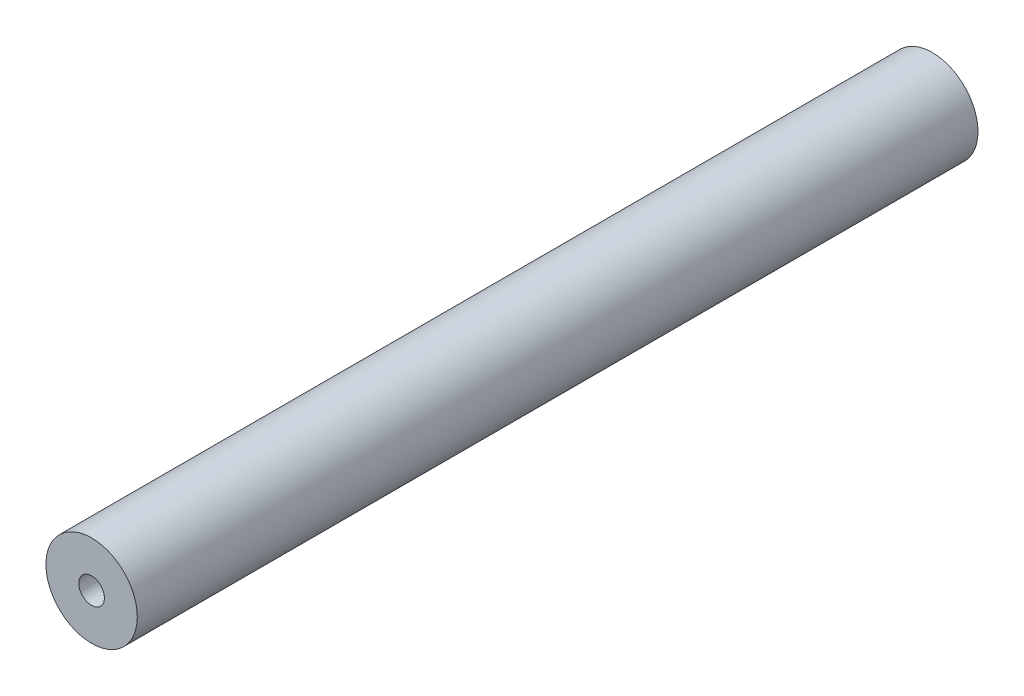
SolidWorks part; units mm, degrees
ref_plane "Front Plane" through (0, 0, 0) normal (0, 0, 1) x (1, 0, 0)
ref_plane "Top Plane" through (0, 0, 0) normal (0, 1, 0) x (1, 0, 0)
ref_plane "Right Plane" through (0, 0, 0) normal (1, 0, 0) x (0, 0, -1)
sketch "Sketch1" plane through (0, 0, 0) normal (0, 0, 1) x (1, 0, 0)
  circle A0 centre (0, 0) radius 31.75
  dimension "D1" = 63.5
extrude "Boss-Extrude1" add sketch "Sketch1" along normal blind 584.2
sketch "Sketch2" plane through (0, 0, 0) normal (0, 0, -1) x (-1, 0, 0)
  circle A0 centre (0, 0) radius 8.89
  dimension "D1" = 17.78
extrude "Cut-Extrude1" cut sketch "Sketch2" against normal through all
